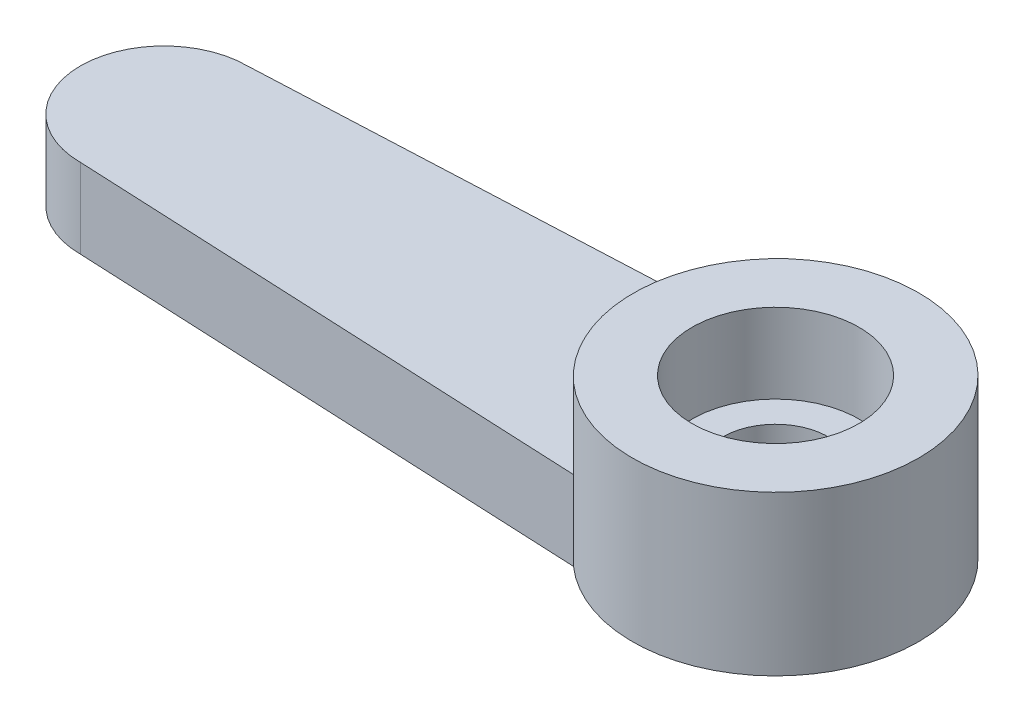
SolidWorks part; units mm, degrees
ref_plane "Front Plane" through (0, 0, 0) normal (0, 0, 1) x (1, 0, 0)
ref_plane "Top Plane" through (0, 0, 0) normal (0, 1, 0) x (1, 0, 0)
ref_plane "Right Plane" through (0, 0, 0) normal (1, 0, 0) x (0, 0, -1)
sketch "Sketch1" plane through (0, 0, 0) normal (0, 1, 0) x (1, 0, 0)
  line L0 (-2.3812, 2.7) -> (-15.3812, 2.1)
  line L1 (-55, 0) -> (55, 0) construction
  line L2 (0, 0) -> (-18.443, 0) construction
  line L3 (-2.3812, -2.7) -> (-15.3812, -2.1)
  arc A0 (-15.3812, 2.1) -> (-15.3812, -2.1) centre (-15.3812, 0) ccw
  circle A1 centre (0, 0) radius 3.6
  dimension "D1" = 2.7
  dimension "D2" = 7.2
  dimension "D3" = 13
  dimension "D4" = 2.1
extrude "Boss-Extrude1" add sketch "Sketch1" along normal mid plane 2
sketch "Sketch2" plane through (0, 1, 0) normal (0, 1, 0) x (1, 0, 0)
  circle A0 centre (0, 0) radius 2.1
  arc A1 (-2.3812, -2.7) -> (-2.3812, 2.7) centre (0, 0) ccw construction
  arc A2 (-2.3812, 2.7) -> (-2.3812, -2.7) centre (0.0624, 0) ccw
  arc M2 (-2.3812, -2.7) -> (-2.3812, 2.7) centre (0, 0) ccw
  dimension "D1" = 1.5
extrude "Boss-Extrude3" add sketch "Sketch2" along normal blind 2 contours A2 A0 M2
sketch "Sketch3" plane through (0, 1, 0) normal (0, 1, 0) x (1, 0, 0)
  circle A0 centre (0, 0) radius 1.325
  dimension "D1" = 2.65
extrude "Cut-Extrude1" cut sketch "Sketch3" against normal through all both and the other way through all
